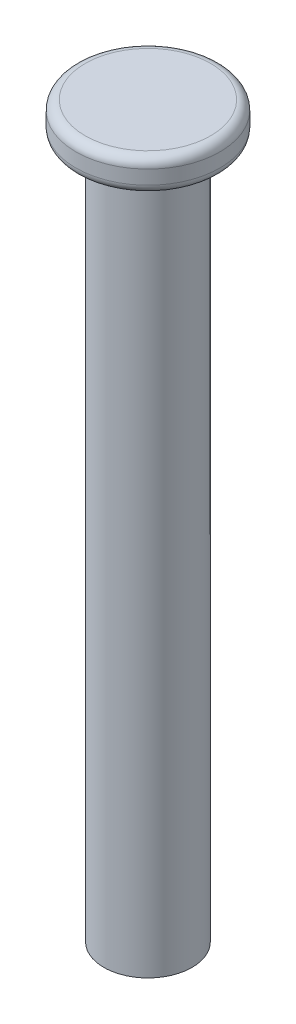
SolidWorks part; units mm, degrees
ref_plane "Front Plane" through (0, 0, 0) normal (0, 0, 1) x (1, 0, 0)
ref_plane "Top Plane" through (0, 0, 0) normal (0, 1, 0) x (1, 0, 0)
ref_plane "Right Plane" through (0, 0, 0) normal (1, 0, 0) x (0, 0, -1)
sketch "Sketch2" plane through (0, 0, 0) normal (0, 1, 0) x (1, 0, 0)
  circle A0 centre (0, 0) radius 1.2065
  dimension "D1" = 2.413
extrude "Boss-Extrude1" add sketch "Sketch2" along normal blind 19.05
sketch "Sketch3" plane through (0, 19.05, 0) normal (0, 1, 0) x (1, 0, 0)
  circle A0 centre (0, 0) radius 1.9685
  dimension "D1" = 3.937
extrude "Boss-Extrude2" add sketch "Sketch3" along normal blind 0.889
fillet "Fillet1" radius 0.254 2 edges at (0, 19.05, 1.9685) (0, 19.939, 1.9685)
